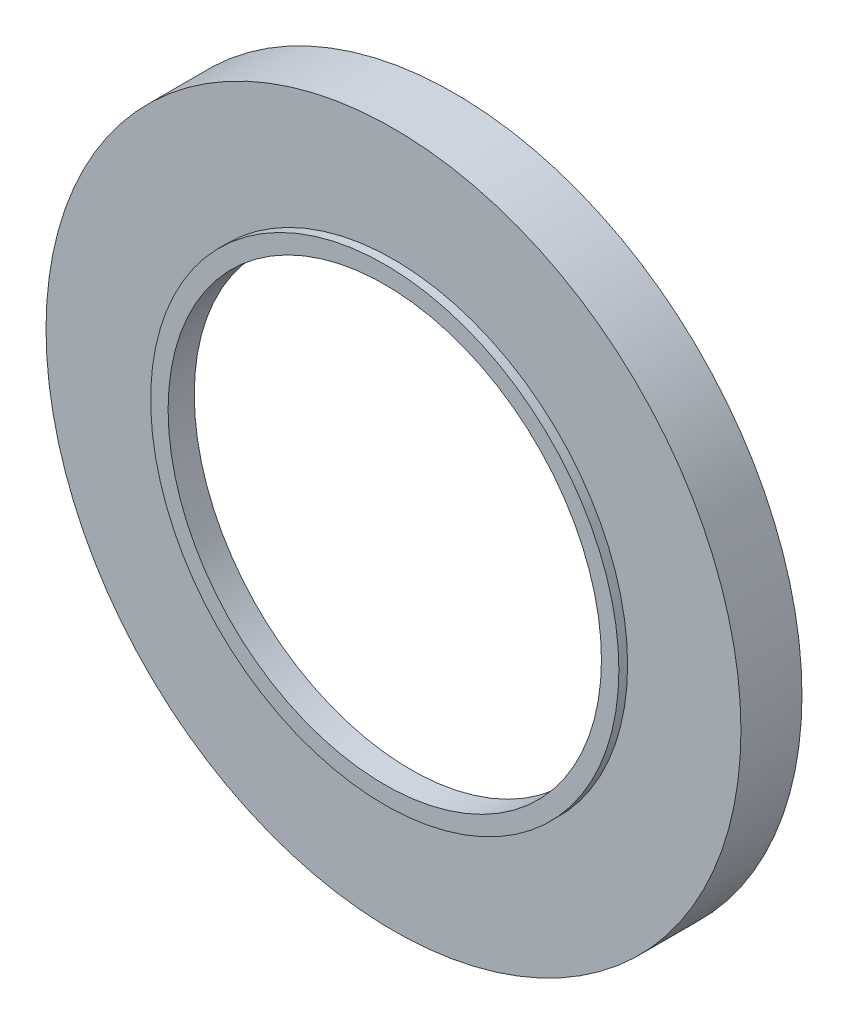
SolidWorks part; units mm, degrees
ref_plane "前视基准面" through (0, 0, 0) normal (0, 0, 1) x (1, 0, 0)
ref_plane "上视基准面" through (0, 0, 0) normal (0, 1, 0) x (1, 0, 0)
ref_plane "右视基准面" through (0, 0, 0) normal (1, 0, 0) x (0, 0, -1)
other "Configuration Table"
sketch "草图1" plane through (0, 0, 0) normal (0, 0, 1) x (1, 0, 0)
  circle A0 centre (0, 0) radius 39.8513
extrude "拉伸-薄壁1" add sketch "草图1" along normal blind 5 thin thin type one direction reverse wall 2
sketch "草图2" plane through (0, 0, 5) normal (0, 0, 1) x (1, 0, 0)
  circle A0 centre (0, 0) radius 39.8513 construction
  circle A1 centre (0, 0) radius 39.8513
extrude "拉伸-薄壁2" add sketch "草图2" along normal blind 2 thin thin type one direction reverse wall 15
sketch "草图3" plane through (0, 0, 7) normal (0, 0, 1) x (1, 0, 0)
  circle A0 centre (0, 0) radius 24.8513 construction
  circle A1 centre (0, 0) radius 24.8513
extrude "拉伸-薄壁3" add sketch "草图3" along normal blind 1 thin
